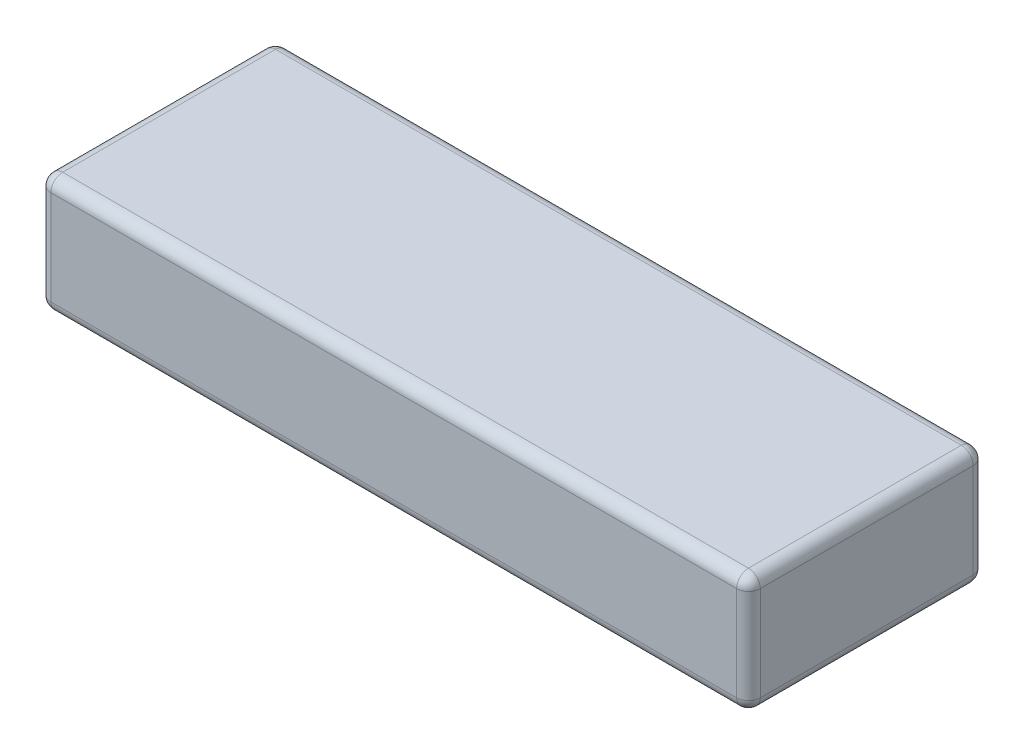
SolidWorks part; units mm, degrees
material "Stainless Steel (ferritic)"
ref_plane "Front Plane" through (0, 0, 0) normal (0, 0, 1) x (1, 0, 0)
ref_plane "Top Plane" through (0, 0, 0) normal (0, 1, 0) x (1, 0, 0)
ref_plane "Right Plane" through (0, 0, 0) normal (1, 0, 0) x (0, 0, -1)
sketch "Sketch1" plane through (0, 0, 0) normal (0, 1, 0) x (1, 0, 0)
  line L1 (-15, -5) -> (15, -5)
  line L2 (-15, -5) -> (-15, 5)
  line L3 (-15, 5) -> (15, 5)
  line L4 (15, -5) -> (15, 5)
  line L5 (-15, -5) -> (15, 5) construction
  line L6 (-15, 5) -> (15, -5) construction
  point P0 (0, 0)
  dimension "D1" = 30
  dimension "D2" = 10
extrude "Boss-Extrude1" add sketch "Sketch1" along normal blind 5
fillet "Fillet1" radius 0.5 12 edges at (15, 2.5, -5) (-15, 2.5, -5) (0, 0, -5) (-15, 0, 0) (15, 0, 0) (-15, 2.5, 5) (15, 2.5, 5) (0, 0, 5) (0, 5, 5) (-15, 5, 0) (0, 5, -5) (15, 5, 0)
